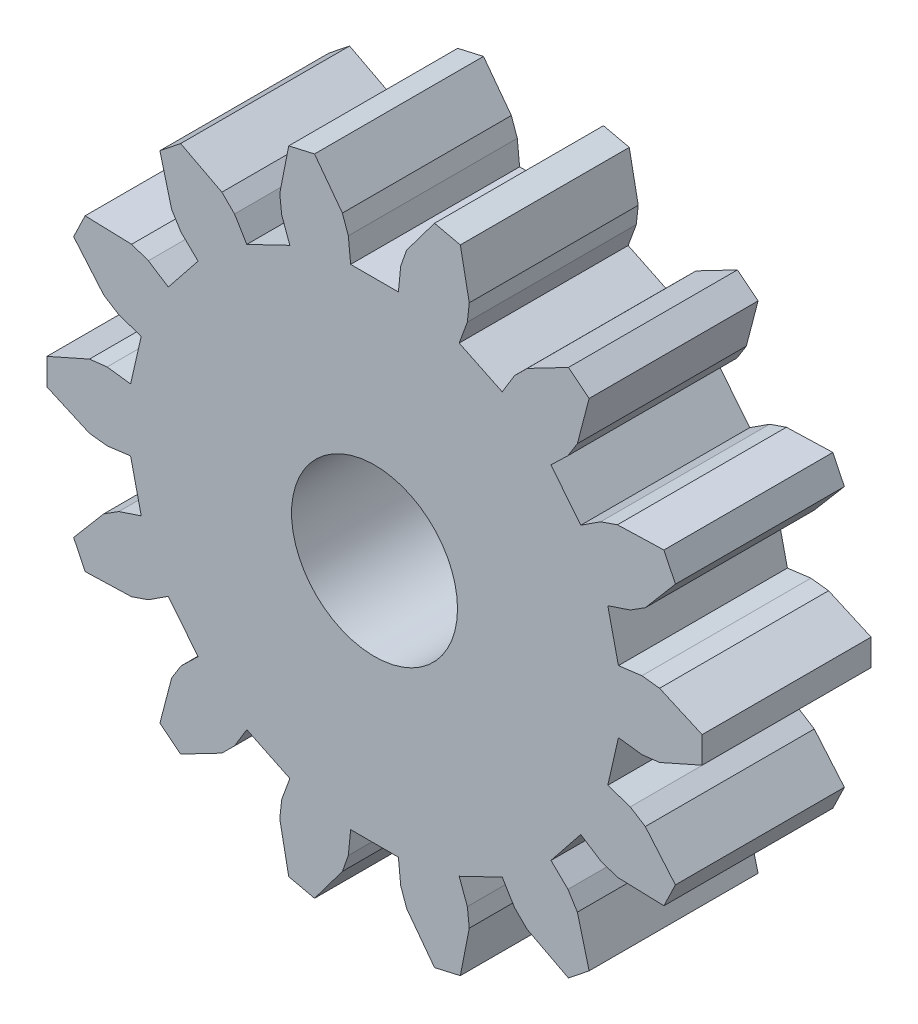
SolidWorks part; units mm, degrees
ref_plane "Front Plane" through (0, 0, 0) normal (0, 0, 1) x (1, 0, 0)
ref_plane "Top Plane" through (0, 0, 0) normal (0, 1, 0) x (1, 0, 0)
ref_plane "Right Plane" through (0, 0, 0) normal (1, 0, 0) x (0, 0, -1)
sketch "Model" plane through (0, 0, 0) normal (0, 0, 1) x (1, 0, 0)
  line L0 (109.3723, 95.1032) -> (110.7626, 95.2808)
  line L1 (110.7626, 95.2808) -> (111.8085, 95.1594)
  line L2 (111.8085, 95.1594) -> (114.325, 94.0416)
  line L3 (114.325, 94.0416) -> (114.325, 92.4752)
  line L4 (114.325, 92.4752) -> (111.8085, 91.3574)
  line L5 (111.8085, 91.3574) -> (110.7626, 91.2359)
  line L6 (110.7626, 91.2359) -> (109.3723, 91.4136)
  line L7 (109.3723, 91.4136) -> (108.7432, 88.657)
  line L8 (108.7432, 88.657) -> (110.0728, 88.2139)
  line L9 (110.0728, 88.2139) -> (110.9625, 87.6507)
  line L10 (110.9625, 87.6507) -> (112.7447, 85.5517)
  line L11 (112.7447, 85.5517) -> (112.0651, 84.1404)
  line L12 (112.0651, 84.1404) -> (109.3128, 84.2252)
  line L13 (109.3128, 84.2252) -> (108.3178, 84.5696)
  line L14 (108.3178, 84.5696) -> (107.1423, 85.3328)
  line L15 (107.1423, 85.3328) -> (105.3794, 83.1223)
  line L16 (105.3794, 83.1223) -> (106.3852, 82.1461)
  line L17 (106.3852, 82.1461) -> (106.9423, 81.2527)
  line L18 (106.9423, 81.2527) -> (107.6374, 78.5883)
  line L19 (107.6374, 78.5883) -> (106.4127, 77.6116)
  line L20 (106.4127, 77.6116) -> (103.9698, 78.8821)
  line L21 (103.9698, 78.8821) -> (103.2227, 79.6241)
  line L22 (103.2227, 79.6241) -> (102.4948, 80.8219)
  line L23 (102.4948, 80.8219) -> (99.9474, 79.5951)
  line L24 (99.9474, 79.5951) -> (100.43, 78.2792)
  line L25 (100.43, 78.2792) -> (100.5443, 77.2325)
  line L26 (100.5443, 77.2325) -> (100.0145, 74.5304)
  line L27 (100.0145, 74.5304) -> (98.4873, 74.1818)
  line L28 (98.4873, 74.1818) -> (96.8376, 76.3865)
  line L29 (96.8376, 76.3865) -> (96.4865, 77.3791)
  line L30 (96.4865, 77.3791) -> (96.3503, 78.7741)
  line L31 (96.3503, 78.7741) -> (93.5229, 78.7741)
  line L32 (93.5229, 78.7741) -> (93.3867, 77.3791)
  line L33 (93.3867, 77.3791) -> (93.0356, 76.3865)
  line L34 (93.0356, 76.3865) -> (91.3859, 74.1818)
  line L35 (91.3859, 74.1818) -> (89.8587, 74.5304)
  line L36 (89.8587, 74.5304) -> (89.3289, 77.2325)
  line L37 (89.3289, 77.2325) -> (89.4432, 78.2792)
  line L38 (89.4432, 78.2792) -> (89.9258, 79.5951)
  line L39 (89.9258, 79.5951) -> (87.3784, 80.8219)
  line L40 (87.3784, 80.8219) -> (86.6505, 79.6241)
  line L41 (86.6505, 79.6241) -> (85.9034, 78.8821)
  line L42 (85.9034, 78.8821) -> (83.4605, 77.6116)
  line L43 (83.4605, 77.6116) -> (82.2358, 78.5883)
  line L44 (82.2358, 78.5883) -> (82.9309, 81.2527)
  line L45 (82.9309, 81.2527) -> (83.488, 82.1461)
  line L46 (83.488, 82.1461) -> (84.4938, 83.1223)
  line L47 (84.4938, 83.1223) -> (82.7309, 85.3328)
  line L48 (82.7309, 85.3328) -> (81.5554, 84.5696)
  line L49 (81.5554, 84.5696) -> (80.5604, 84.2252)
  line L50 (80.5604, 84.2252) -> (77.8081, 84.1404)
  line L51 (77.8081, 84.1404) -> (77.1285, 85.5517)
  line L52 (77.1285, 85.5517) -> (78.9107, 87.6507)
  line L53 (78.9107, 87.6507) -> (79.8003, 88.2139)
  line L54 (79.8003, 88.2139) -> (81.13, 88.657)
  line L55 (81.13, 88.657) -> (80.5009, 91.4136)
  line L56 (80.5009, 91.4136) -> (79.1106, 91.2359)
  line L57 (79.1106, 91.2359) -> (78.0647, 91.3574)
  line L58 (78.0647, 91.3574) -> (75.5482, 92.4752)
  line L59 (75.5482, 92.4752) -> (75.5482, 94.0416)
  line L60 (75.5482, 94.0416) -> (78.0647, 95.1594)
  line L61 (78.0647, 95.1594) -> (79.1106, 95.2808)
  line L62 (79.1106, 95.2808) -> (80.5009, 95.1032)
  line L63 (80.5009, 95.1032) -> (81.13, 97.8597)
  line L64 (81.13, 97.8597) -> (79.8003, 98.3029)
  line L65 (79.8003, 98.3029) -> (78.9107, 98.8661)
  line L66 (78.9107, 98.8661) -> (77.1285, 100.965)
  line L67 (77.1285, 100.965) -> (77.8081, 102.3763)
  line L68 (77.8081, 102.3763) -> (80.5604, 102.2916)
  line L69 (80.5604, 102.2916) -> (81.5554, 101.9472)
  line L70 (81.5554, 101.9472) -> (82.7309, 101.1839)
  line L71 (82.7309, 101.1839) -> (84.4938, 103.3945)
  line L72 (84.4938, 103.3945) -> (83.488, 104.3707)
  line L73 (83.488, 104.3707) -> (82.9309, 105.2641)
  line L74 (82.9309, 105.2641) -> (82.2358, 107.9285)
  line L75 (82.2358, 107.9285) -> (83.4605, 108.9051)
  line L76 (83.4605, 108.9051) -> (85.9034, 107.6346)
  line L77 (85.9034, 107.6346) -> (86.6505, 106.8926)
  line L78 (86.6505, 106.8926) -> (87.3784, 105.6949)
  line L79 (87.3784, 105.6949) -> (89.9258, 106.9217)
  line L80 (89.9258, 106.9217) -> (89.4432, 108.2376)
  line L81 (89.4432, 108.2376) -> (89.3289, 109.2842)
  line L82 (89.3289, 109.2842) -> (89.8587, 111.9863)
  line L83 (89.8587, 111.9863) -> (91.3859, 112.3349)
  line L84 (91.3859, 112.3349) -> (93.0356, 110.1303)
  line L85 (93.0356, 110.1303) -> (93.3867, 109.1376)
  line L86 (93.3867, 109.1376) -> (93.5229, 107.7427)
  line L87 (93.5229, 107.7427) -> (96.3503, 107.7427)
  line L88 (96.3503, 107.7427) -> (96.4865, 109.1376)
  line L89 (96.4865, 109.1376) -> (96.8376, 110.1303)
  line L90 (96.8376, 110.1303) -> (98.4873, 112.3349)
  line L91 (98.4873, 112.3349) -> (100.0145, 111.9863)
  line L92 (100.0145, 111.9863) -> (100.5443, 109.2842)
  line L93 (100.5443, 109.2842) -> (100.43, 108.2376)
  line L94 (100.43, 108.2376) -> (99.9474, 106.9217)
  line L95 (99.9474, 106.9217) -> (102.4948, 105.6949)
  line L96 (102.4948, 105.6949) -> (103.2227, 106.8926)
  line L97 (103.2227, 106.8926) -> (103.9698, 107.6346)
  line L98 (103.9698, 107.6346) -> (106.4127, 108.9051)
  line L99 (106.4127, 108.9051) -> (107.6374, 107.9285)
  line L100 (107.6374, 107.9285) -> (106.9423, 105.2641)
  line L101 (106.9423, 105.2641) -> (106.3852, 104.3707)
  line L102 (106.3852, 104.3707) -> (105.3794, 103.3945)
  line L103 (105.3794, 103.3945) -> (107.1423, 101.1839)
  line L104 (107.1423, 101.1839) -> (108.3178, 101.9472)
  line L105 (108.3178, 101.9472) -> (109.3128, 102.2916)
  line L106 (109.3128, 102.2916) -> (112.0651, 102.3763)
  line L107 (112.0651, 102.3763) -> (112.7447, 100.965)
  line L108 (112.7447, 100.965) -> (110.9625, 98.8661)
  line L109 (110.9625, 98.8661) -> (110.0728, 98.3029)
  line L110 (110.0728, 98.3029) -> (108.7432, 97.8597)
  line L111 (108.7432, 97.8597) -> (109.3723, 95.1032)
  circle A0 centre (94.9366, 93.2584) radius 4.9116
extrude "Boss-Extrude1" add sketch "Model" along normal blind 10 contours L111 L110 L109 L108 L107 L106 L105 L104 L103 L102 L101 L100 L99 L98 L97 L96 L95 L94 L93 L92 L91 L90 L89 L88 L87 L86 L85 L84 L83 L82 L81 L80 L79 L78 L77 L76 L75 L74 L73 L72 L71 L70 L69 L68 L67 L66 L65 L64 L63 L62 L61
